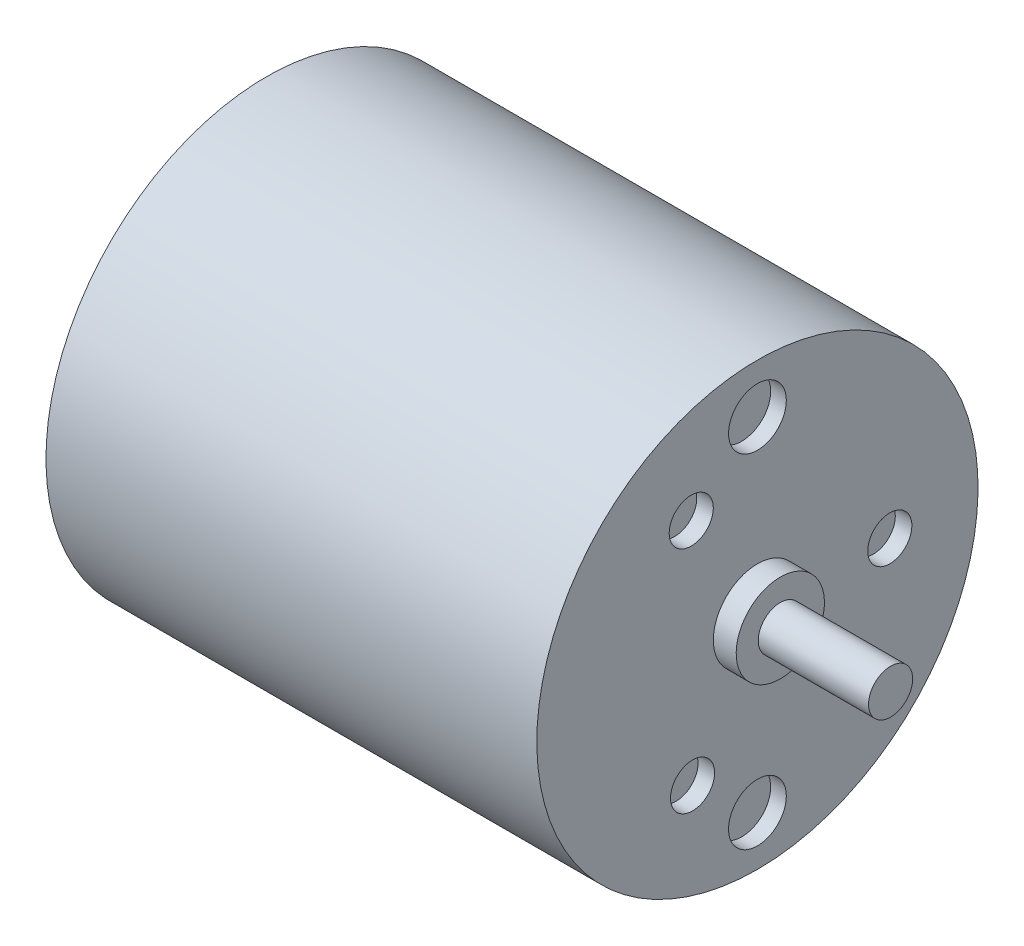
SolidWorks part; units mm, degrees
ref_plane "Front Plane" through (0, 0, 0) normal (0, 0, 1) x (1, 0, 0)
ref_plane "Top Plane" through (0, 0, 0) normal (0, 1, 0) x (1, 0, 0)
ref_plane "Right Plane" through (0, 0, 0) normal (1, 0, 0) x (0, 0, -1)
sketch "Sketch1" plane through (0, 0, 0) normal (0, 0, 1) x (1, 0, 0)
  line L0 (-107.4443, 9.2194) -> (90.6031, 9.2194) construction
  line L1 (-74.1631, 49.2194) -> (14.8369, 49.2194)
  line L2 (-74.1631, 49.2194) -> (-74.1631, 9.2194)
  line L3 (-74.1631, 9.2194) -> (14.8369, 9.2194)
  line L4 (14.8369, 49.2194) -> (14.8369, 9.2194)
  line L5 (-74.1631, 29.2194) -> (-84.6631, 29.2194)
  line L6 (-74.1631, 29.2194) -> (-74.1631, 9.2194)
  line L7 (-74.1631, 9.2194) -> (-84.6631, 9.2194)
  line L8 (-84.6631, 29.2194) -> (-84.6631, 9.2194)
  line L9 (14.8369, 17.2194) -> (18.9852, 17.2194)
  line L10 (14.8369, 17.2194) -> (14.8369, 9.2194)
  line L11 (14.8369, 9.2194) -> (18.9852, 9.2194)
  line L12 (18.9852, 17.2194) -> (18.9852, 9.2194)
  line L13 (18.9852, 13.2194) -> (38.9852, 13.2194)
  line L14 (18.9852, 13.2194) -> (18.9852, 9.2194)
  line L15 (18.9852, 9.2194) -> (38.9852, 9.2194)
  line L16 (38.9852, 13.2194) -> (38.9852, 9.2194)
  line L18 (-74.1631, 49.2194) -> (-66.7957, 49.2194)
  line L19 (-74.1631, 49.2194) -> (-74.1631, 9.2194)
  line L20 (-74.1631, 9.2194) -> (-66.7957, 9.2194)
  line L21 (-66.7957, 49.2194) -> (-66.7957, 9.2194)
  line L22 (14.8369, 49.2194) -> (6.9308, 49.2194)
  line L23 (14.8369, 49.2194) -> (14.8369, 9.2194)
  line L24 (14.8369, 9.2194) -> (6.9308, 9.2194)
  line L25 (6.9308, 49.2194) -> (6.9308, 9.2194)
  point P13 (-84.6631, 19.2194)
  dimension "D1" = 89
  dimension "D2" = 10
  dimension "D3" = 40
  dimension "D4" = 20
  dimension "D5" = 4.1483
  dimension "D6" = 4
  dimension "D7" = 10.5
  dimension "D8" = 40
revolve "Revolve2" add sketch "Sketch1" angle 360 about L0
ref_plane "Plane1" through (15, 0, 0) normal (1, 0, 0) x (0, 0, -1)
sketch "Sketch4" plane through (15, 0, 0) normal (1, 0, 0) x (0, 0, -1)
  line L0 (-40, 9.2194) -> (40, 9.2194) construction
  circle A0 centre (0, 40.2788) radius 5.2366
  circle A1 centre (0, 9.2194) radius 40 construction
  circle A2 centre (0, -21.8399) radius 5.2366
extrude "Cut-Extrude3" cut sketch "Sketch4" against normal blind 3 contours A0 | A2
sketch "Sketch7" plane through (14.8369, 0, 0) normal (1, 0, 0) x (0, 0, -1)
  line L0 (-12, 30.004) -> (0, 9.2194) construction
  line L1 (0, 9.2194) -> (24, 9.2194) construction
  line L2 (0, 9.2194) -> (-11.7625, -11.7005) construction
  circle A0 centre (-12, 30.004) radius 4
  circle A1 centre (-11.7625, -11.7005) radius 4
  circle A2 centre (24, 9.2194) radius 4
  dimension "D1" = 8
  dimension "D2" = 8
  dimension "D3" = 8
extrude "Cut-Extrude4" cut sketch "Sketch7" against normal blind 3 contours A1 | A0 | A2
